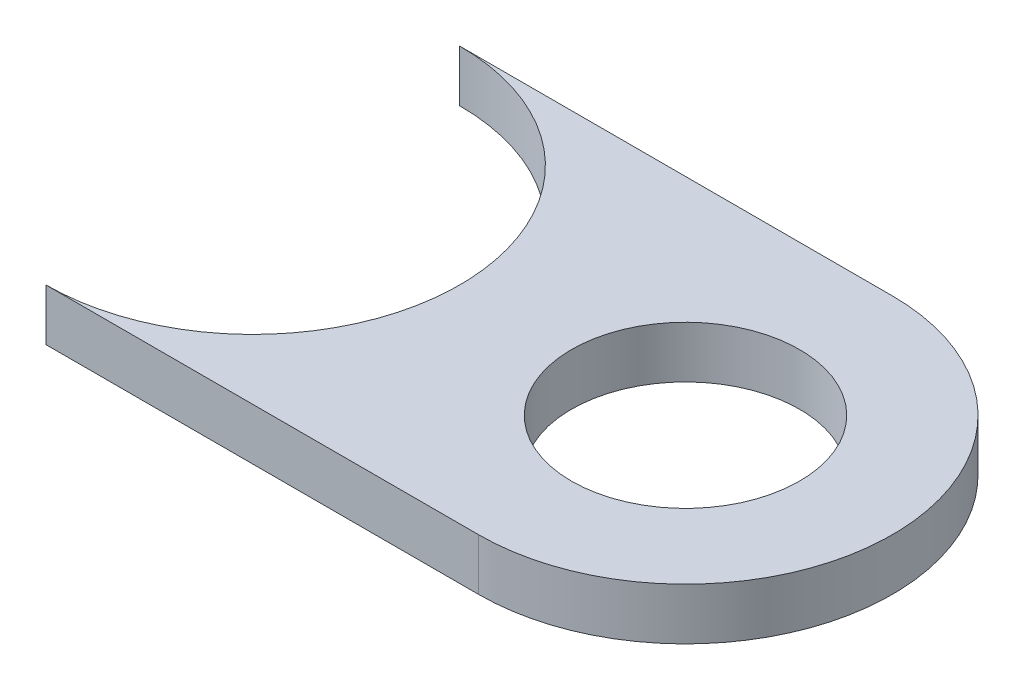
SolidWorks part; units mm, degrees
ref_plane "Front Plane" through (0, 0, 0) normal (0, 0, 1) x (1, 0, 0)
ref_plane "Top Plane" through (0, 0, 0) normal (0, 1, 0) x (1, 0, 0)
ref_plane "Right Plane" through (0, 0, 0) normal (1, 0, 0) x (0, 0, -1)
sketch "Sketch1" plane through (0, 0, 0) normal (0, 1, 0) x (1, 0, 0)
  line L0 (0, 0) -> (-26.5608, 0) construction
  line L1 (-26.5608, 12.7) -> (0, 12.7)
  line L2 (-26.5608, -12.7) -> (0, -12.7)
  circle A0 centre (0, 0) radius 7.0002
  arc A1 (-26.5608, -12.7) -> (-26.5608, 12.7) centre (-26.5608, 0) ccw
  arc A2 (0, -12.7) -> (0, 12.7) centre (0, 0) ccw
extrude "Boss-Extrude1" add sketch "Sketch1" along normal blind 3.175
sketch "Sketch2" plane through (0, 3.175, 0) normal (0, 1, 0) x (1, 0, 0)
  line L0 (0, -12.7) -> (0, -9.525)
  line L1 (0, -9.525) -> (-18.1605, -9.525)
  arc A0 (-26.5608, -12.7) -> (-26.5608, 12.7) centre (-26.5608, 0) ccw construction
  dimension "D1" = 18.1605
